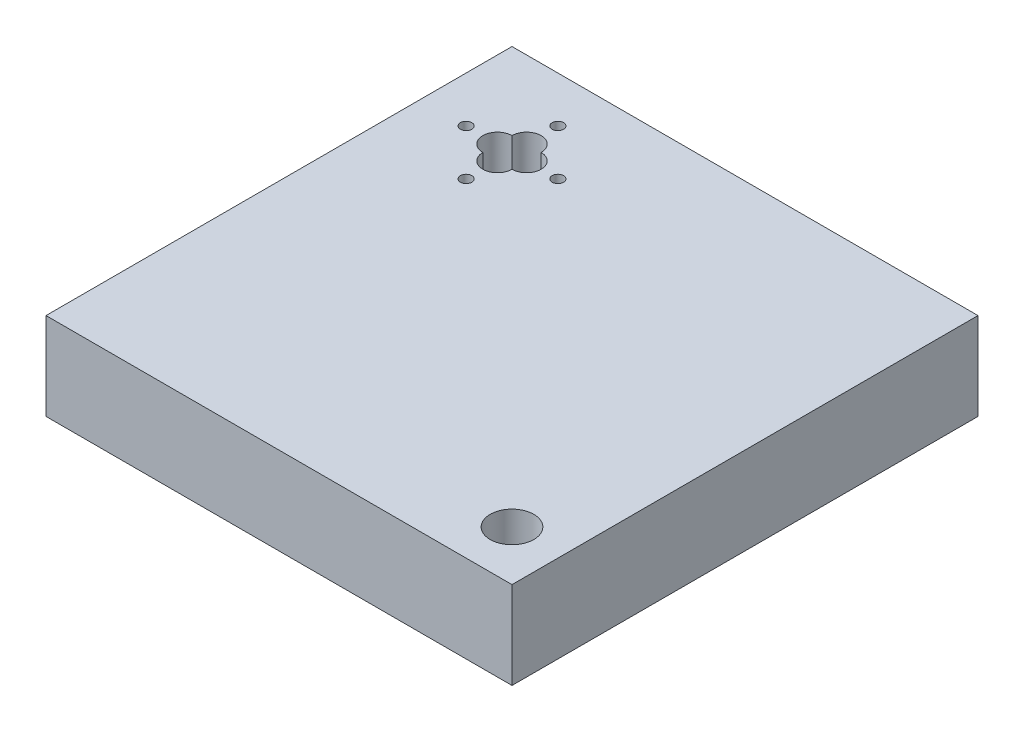
SolidWorks part; units mm, degrees
other "Markup1"
sketch "Sketch6" plane through (50.3553, 0, 50.3553) normal (0.291, 0.9567, 0.0091) x (0.9567, -0.291, -0.0015)
material "6061 Alloy"
ref_plane "Front Plane" through (0, 0, 0) normal (0, 0, 1) x (1, 0, 0)
ref_plane "Top Plane" through (0, 0, 0) normal (0, 1, 0) x (1, 0, 0)
ref_plane "Right Plane" through (0, 0, 0) normal (1, 0, 0) x (0, 0, -1)
sketch "Sketch2" plane through (0, 0, 0) normal (0, 1, 0) x (1, 0, 0)
  line L0 (0, 0) -> (70.7107, -70.7107) construction
  line L1 (-3.18, 3.18) -> (3.18, 3.18)
  line L2 (-3.18, 3.18) -> (-3.18, -3.18)
  line L3 (-3.18, -3.18) -> (3.18, -3.18)
  line L4 (3.18, 3.18) -> (3.18, -3.18)
  line L5 (0, 0) -> (70.7107, 0) construction
  line L6 (-12.3744, -12.3744) -> (12.3744, 12.3744) construction
  line L7 (12.3744, 12.3744) -> (83.085, -58.3363) construction
  line L8 (-12.3744, -12.3744) -> (58.3363, -83.085) construction
  line L10 (-20, 20) -> (81.6, 20)
  line L11 (-20, 20) -> (-20, -81.6)
  line L12 (-20, -81.6) -> (81.6, -81.6)
  line L13 (81.6, 20) -> (81.6, -81.6)
  line L14 (0, 0) -> (-20, 0) construction
  line L16 (0, 0) -> (0, 20) construction
  circle A0 centre (70.7107, -70.7107) radius 4.7625
  arc A1 (12.3744, 12.3744) -> (-12.3744, -12.3744) centre (0, 0) ccw construction
  arc A2 (83.085, -58.3363) -> (58.3363, -83.085) centre (70.7107, -70.7107) cw construction
  circle A3 centre (0, 10) radius 1.5 construction
  circle A4 centre (-10, 0) radius 1.5 construction
  circle A5 centre (0, 0) radius 10 construction
  circle A8 centre (70.7107, -70.7107) radius 37 construction
  circle A9 centre (10, 0) radius 1.5 construction
  circle A10 centre (0, -10) radius 1.5 construction
  arc A11 (-3.18, 3.18) -> (-3.18, -3.18) centre (-3.18, 0) ccw
  arc A12 (3.18, 3.18) -> (-3.18, 3.18) centre (0, 3.18) ccw
  arc A13 (3.18, -3.18) -> (3.18, 3.18) centre (3.18, 0) ccw
  arc A14 (-3.18, -3.18) -> (3.18, -3.18) centre (0, -3.18) ccw
  point P4 (0, 3.18)
  point P6 (3.18, 0)
  point P13 (0, 0)
  point P45 (0, 0)
  dimension "D4" = 9.525
  dimension "D5" = 17.5
  dimension "D6" = 17.5
  dimension "D7" = 3
  dimension "D8" = 20
  dimension "D9" = 74
  dimension "D10" = 20
  dimension "D12" = 4
  dimension "D1" = 6.36
  dimension "D2" = 45
  dimension "D3" = 100
  dimension "D11" = 101.6
extrude "Boss-Extrude1" add sketch "Sketch2" against normal blind 19.05 contours L13 L10 L11 L12 A14 A11 A12 A13 A0 | A1 L8 A2 L7
hole_wizard "Tap Drill for M3x0.5 Tap1" positions "3DSketch1" profile "Sketch7" hole size "M3x0.5" standard "ANSI Metric" end condition up to next
sketch3d "3DSketch1"
  point P18 (0, 0, -10)
  point P20 (10, 0, 0)
  point P22 (0, 0, 10)
  point P24 (-10, 0, 0)
  point P27 (-10, 0, 0)
  point P29 (0, 0, -10)
  point P31 (10, 0, 0)
  point P33 (0, 0, 10)
sketch "Sketch7" plane through (0, 0, -10) normal (1, 0, 0) x (0, 0, 1)
  line L0 (0, 0) -> (0, 19.05)
  line L1 (0, 19.05) -> (1.25, 19.05)
  line L2 (1.25, 19.05) -> (1.25, 0)
  line L5 (1.25, 0) -> (0, 0)
  line L11 (0, -6.35) -> (0, 107.95) construction
  dimension "Thru Hole Dia." = 2.5
  dimension "Thru Hole Depth" = 19.05
